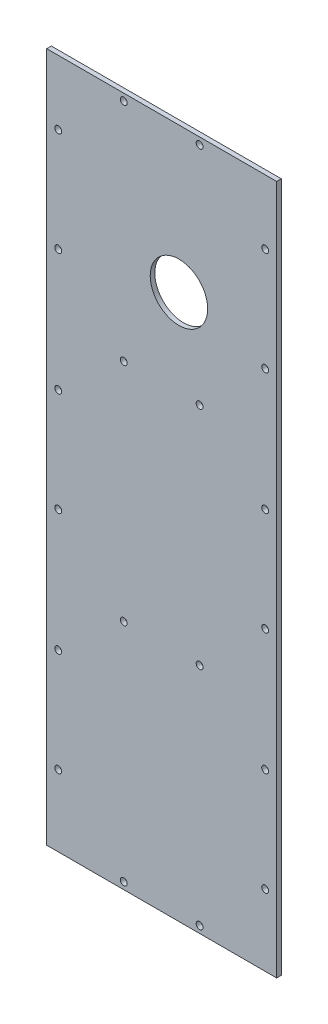
SolidWorks part; units mm, degrees
ref_plane "Front Plane" through (0, 0, 0) normal (0, 0, 1) x (1, 0, 0)
ref_plane "Top Plane" through (0, 0, 0) normal (0, 1, 0) x (1, 0, 0)
ref_plane "Right Plane" through (0, 0, 0) normal (1, 0, 0) x (0, 0, -1)
sketch "Sketch1" plane through (0, 0, 0) normal (0, 0, 1) x (1, 0, 0)
  line L1 (50, -150) -> (-50, -150)
  line L2 (50, -150) -> (50, 150)
  line L3 (50, 150) -> (-50, 150)
  line L4 (-50, -150) -> (-50, 150)
  line L5 (50, -150) -> (-50, 150) construction
  line L6 (50, 150) -> (-50, -150) construction
  point P0 (0, 0)
  dimension "D1" = 100
  dimension "D2" = 300
extrude "Boss-Extrude1" add sketch "Sketch1" along normal blind 2
sketch "Sketch2" plane through (0, 0, 2) normal (0, 0, 1) x (1, 0, 0)
  line L0 (-50, 150) -> (-50, -150) construction
  line L1 (50, 150) -> (-50, 150) construction
  line L2 (-50, -150) -> (50, -150) construction
  line L4 (0, -55) -> (0, 55) construction
  circle A0 centre (-45, 122) radius 1.5
  circle A1 centre (-45, 77) radius 1.5
  circle A2 centre (45, 122) radius 1.5
  circle A3 centre (45, 77) radius 1.5
  circle A4 centre (-45, 24) radius 1.5
  circle A5 centre (-45, -21) radius 1.5
  circle A6 centre (45, 24) radius 1.5
  circle A7 centre (45, -21) radius 1.5
  circle A8 centre (-45, -74) radius 1.5
  circle A9 centre (-45, -119) radius 1.5
  circle A10 centre (45, -74) radius 1.5
  circle A11 centre (45, -119) radius 1.5
  circle A13 centre (16.5, -147) radius 1.5
  circle A14 centre (-16.5, -147) radius 1.5
  circle A15 centre (-16.5, -49) radius 1.5
  circle A16 centre (16.5, -49) radius 1.5
  circle A17 centre (-16.5, 49) radius 1.5
  circle A18 centre (16.5, 49) radius 1.5
  circle A19 centre (-16.5, 147) radius 1.5
  circle A20 centre (16.5, 147) radius 1.5
  dimension "D1" = 3
  dimension "D3" = 28
  dimension "D4" = 3
  dimension "D6" = 5
  dimension "D10" = 3
  dimension "D11" = 33
  dimension "D13" = 3
  dimension "D2" = 5
  dimension "D5" = 45
  dimension "D9" = 31
  dimension "D7" = 2
  dimension "D8" = 3
  dimension "D12" = 4
extrude "Cut-Extrude1" cut sketch "Sketch2" against normal blind 10
sketch "Sketch3" plane through (0, 0, 0) normal (0, 0, -1) x (-1, 0, 0)
  line L0 (-50, 150) -> (50, 150) construction
  line L1 (-50, -150) -> (-50, 150) construction
  circle A0 centre (-7.5, 87) radius 12.5
  dimension "D2" = 25
  dimension "D3" = 42.5
  dimension "D1" = 63
extrude "Cut-Extrude2" cut sketch "Sketch3" against normal blind 10
